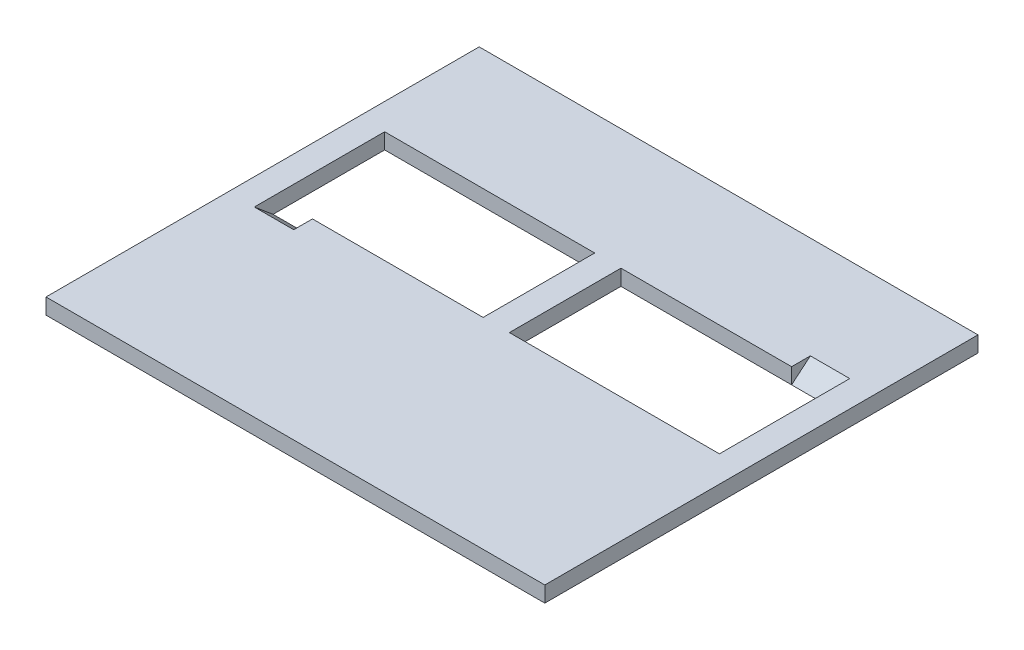
SolidWorks part; units mm, degrees
ref_plane "Front Plane" through (0, 0, 0) normal (0, 0, 1) x (1, 0, 0)
ref_plane "Top Plane" through (0, 0, 0) normal (0, 1, 0) x (1, 0, 0)
ref_plane "Right Plane" through (0, 0, 0) normal (1, 0, 0) x (0, 0, -1)
sketch "Sketch1" plane through (0, 0, 0) normal (0, 1, 0) x (1, 0, 0)
  line L0 (85, -6) -> (5, -6)
  line L1 (95, 82.5) -> (-95, 82.5)
  line L2 (95, 82.5) -> (95, -82.5)
  line L3 (95, -82.5) -> (-95, -82.5)
  line L4 (-95, 82.5) -> (-95, -82.5)
  line L5 (0, -82.5) -> (0, 82.5) construction
  line L6 (95, 0) -> (-95, 0) construction
  line L7 (-85, 36.5) -> (-5, 36.5)
  line L8 (-85, 36.5) -> (-85, -6)
  line L9 (-85, -6) -> (-5, -6)
  line L10 (-5, 36.5) -> (-5, -6)
  line L11 (-45, -6) -> (-45, 36.5) construction
  line L12 (-85, 15.25) -> (-5, 15.25) construction
  line L13 (5, 36.5) -> (5, -6)
  line L14 (85, 36.5) -> (5, 36.5)
  line L15 (85, 36.5) -> (85, -6)
  point P0 (0, 0)
  point P4 (-45, 15.25)
  point P12 (85, -6.9576)
  point P13 (86, 36.3004)
  point P14 (85, -8.3366)
  dimension "D1" = 190
  dimension "D2" = 165
  dimension "D3" = 80
  dimension "D4" = 42.5
  dimension "D5" = 10
  dimension "D6" = 46
extrude "Boss-Extrude1" add sketch "Sketch1" along normal blind 6
sketch "Sketch2" plane through (85, 0, 0) normal (-1, 0, 0) x (0, 0, 1)
  line L0 (-43.6505, 6) -> (-36.5, 0)
  line L1 (82.5, 6) -> (-82.5, 6) construction
  line L2 (82.5, 0) -> (-82.5, 0) construction
  line L3 (-36.5, 0) -> (-36.5, 6)
  line L4 (-36.5, 6) -> (-43.6505, 6)
  point P7 (-39.1849, 6)
  point P8 (-40.7122, 6)
  point P9 (-30.5117, 0)
  point P10 (-32.3677, 0)
  point P11 (-32.9134, 6)
  point P13 (-32.9134, 0)
  point P14 (-43.3598, 6)
  dimension "D1" = 40
extrude "Cut-Extrude1" cut sketch "Sketch2" along normal blind 15
sketch "Sketch3" plane through (-85, 0, 0) normal (1, 0, 0) x (0, 0, -1)
  line L4 (-6, 0) -> (-13.1505, 6)
  line L5 (82.5, 6) -> (-82.5, 6) construction
  line L9 (-6, 0) -> (-6, 6)
  line L10 (-6, 6) -> (-13.1505, 6)
  point P1 (-6, 6)
  point P3 (-6, 0)
  point P4 (-24.3786, 6)
  dimension "D1" = 40
extrude "Cut-Extrude2" cut sketch "Sketch3" along normal blind 15
